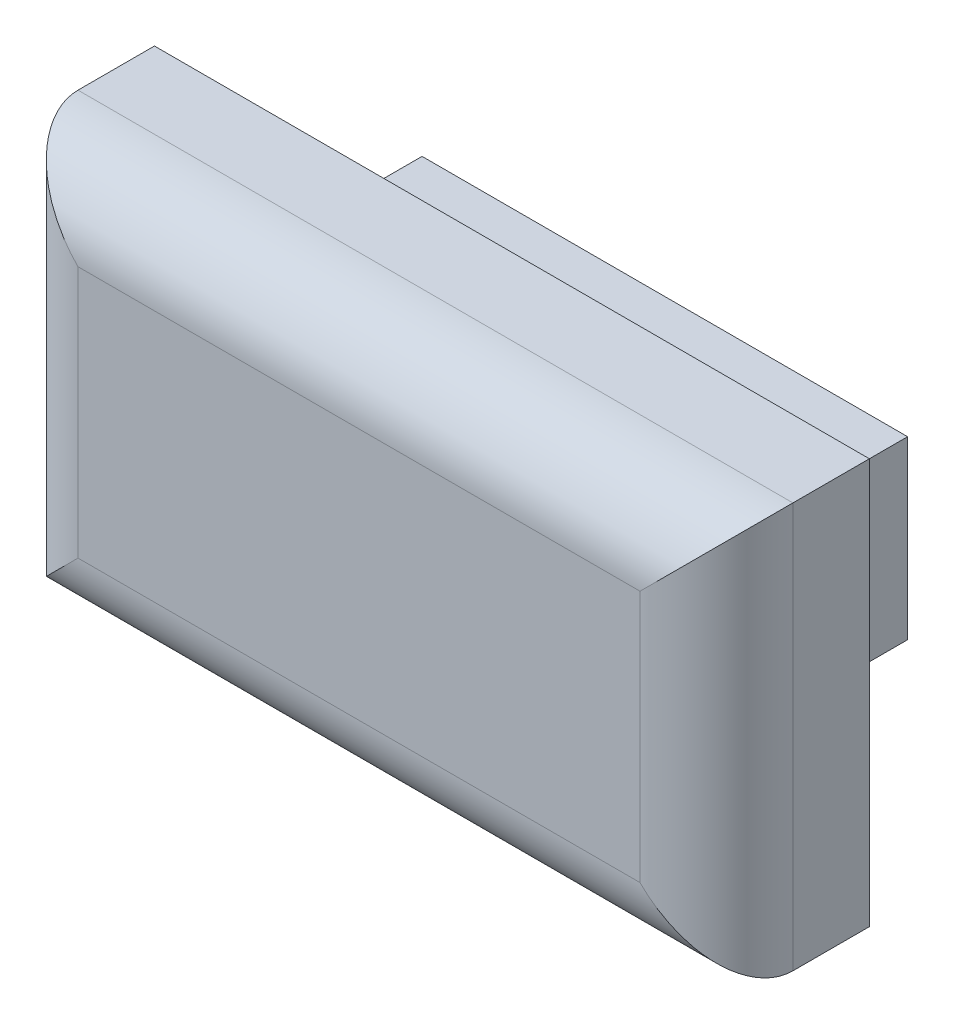
SolidWorks part; units mm, degrees
ref_plane "Front Plane" through (0, 0, 0) normal (0, 0, 1) x (1, 0, 0)
ref_plane "Top Plane" through (0, 0, 0) normal (0, 1, 0) x (1, 0, 0)
ref_plane "Right Plane" through (0, 0, 0) normal (1, 0, 0) x (0, 0, -1)
sketch "Sketch2" plane through (0, 0, 0) normal (0, 0, 1) x (1, 0, 0)
  line L1 (-5.4796, 0.2769) -> (0.8704, 0.2769)
  line L2 (-5.4796, 0.2769) -> (-5.4796, -2.0231)
  line L3 (-5.4796, -2.0231) -> (0.8704, -2.0231)
  line L4 (0.8704, 0.2769) -> (0.8704, -2.0231)
  dimension "D1" = 6.35
  dimension "D2" = 2.3
extrude "Boss-Extrude1" add sketch "Sketch2" along normal blind 2
sketch "Sketch4" plane through (0, 0, 2) normal (0, 0, 1) x (1, 0, 0)
  line L0 (2.3704, 1.7769) -> (-6.9796, 1.7769)
  line L1 (-6.9796, 1.7769) -> (-6.9796, -3.5231)
  line L2 (-6.9796, -3.5231) -> (2.3704, -3.5231)
  line L3 (2.3704, -3.5231) -> (2.3704, 1.7769)
extrude "Boss-Extrude3" add sketch "Sketch4" along normal blind 2
fillet "Fillet1" radius 1 4 edges at (2.3704, -0.8731, 4) (-2.3046, -3.5231, 4) (-6.9796, -0.8731, 4) (-2.3046, 1.7769, 4)
